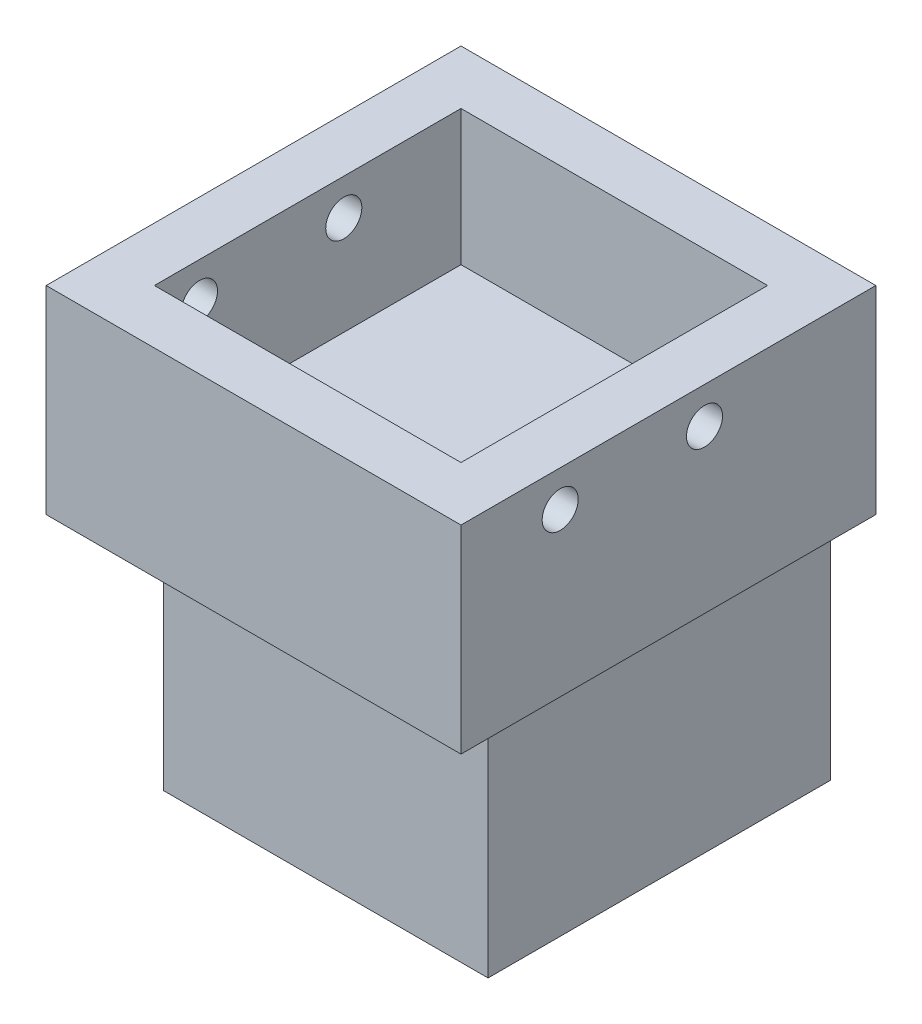
SolidWorks part; units mm, degrees
ref_plane "Front Plane" through (0, 0, 0) normal (0, 0, 1) x (1, 0, 0)
ref_plane "Top Plane" through (0, 0, 0) normal (0, 1, 0) x (1, 0, 0)
ref_plane "Right Plane" through (0, 0, 0) normal (1, 0, 0) x (0, 0, -1)
sketch "Sketch1" plane through (0, 0, 0) normal (0, 1, 0) x (1, 0, 0)
  line L1 (-1.1683, 0.9017) -> (21.8317, 0.9017)
  line L2 (-1.1683, 0.9017) -> (-1.1683, -22.0983)
  line L3 (-1.1683, -22.0983) -> (21.8317, -22.0983)
  line L4 (21.8317, 0.9017) -> (21.8317, -22.0983)
  dimension "D1" = 23
extrude "Boss-Extrude1" add sketch "Sketch1" against normal blind 11
sketch "Sketch2" plane through (0, 0, 0) normal (0, 1, 0) x (1, 0, 0)
  line L0 (-1.1683, 0.9017) -> (-1.1683, -22.0983) construction
  line L1 (1.8317, -2.0983) -> (18.8317, -2.0983)
  line L2 (1.8317, -2.0983) -> (1.8317, -19.0983)
  line L3 (1.8317, -19.0983) -> (18.8317, -19.0983)
  line L4 (18.8317, -2.0983) -> (18.8317, -19.0983)
  line L5 (21.8317, -22.0983) -> (21.8317, 0.9017) construction
  line L6 (21.8317, 0.9017) -> (-1.1683, 0.9017) construction
  dimension "D1" = 3
  dimension "D2" = 3
  dimension "D3" = 3
extrude "Cut-Extrude1" cut sketch "Sketch2" against normal blind 7.5
sketch "Sketch3" plane through (0, -11, 0) normal (0, -1, 0) x (1, 0, 0)
  line L1 (1.3317, -0.9017) -> (19.3317, -0.9017)
  line L2 (1.3317, -0.9017) -> (1.3317, 18.0983)
  line L3 (1.3317, 18.0983) -> (19.3317, 18.0983)
  line L4 (19.3317, -0.9017) -> (19.3317, 18.0983)
  line L5 (-1.1683, 22.0983) -> (21.8317, 22.0983) construction
  line L6 (-1.1683, -0.9017) -> (-1.1683, 22.0983) construction
  line L7 (21.8317, 22.0983) -> (21.8317, -0.9017) construction
  point P4 (-1.1683, -0.9017)
  point P6 (21.8317, -0.9017)
  dimension "D1" = 4
  dimension "D2" = 2.5
  dimension "D3" = 2.5
extrude "Boss-Extrude2" add sketch "Sketch3" along normal blind 14
sketch "Sketch4" plane through (-1.1683, 0, 0) normal (-1, 0, 0) x (0, 0, 1)
  line L0 (22.0983, -11) -> (22.0983, 0) construction
  circle A0 centre (8.5983, -2.0069) radius 1
  circle A1 centre (16.5983, -2.0069) radius 1
  point P4 (0, 0)
  dimension "D1" = 2
  dimension "D2" = 5.5
  dimension "D3" = 8
extrude "Cut-Extrude2" cut sketch "Sketch4" against normal blind 23
